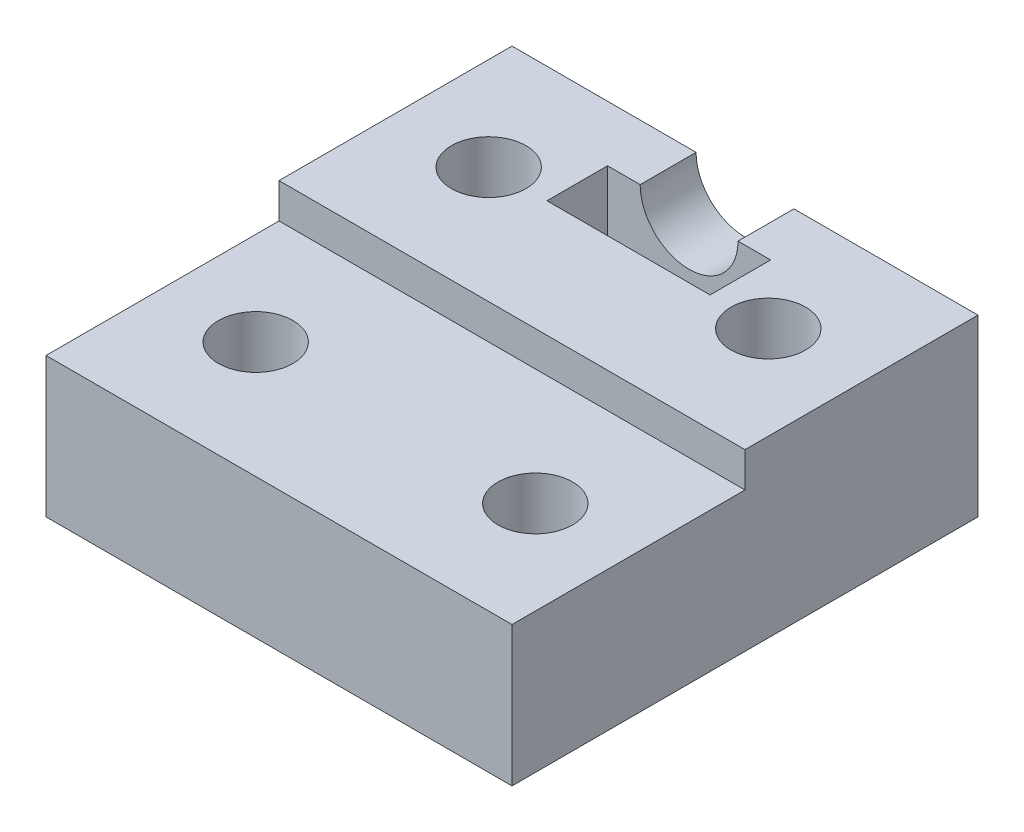
SolidWorks part; units mm, degrees
ref_plane "Front Plane" through (0, 0, 0) normal (0, 0, 1) x (1, 0, 0)
ref_plane "Top Plane" through (0, 0, 0) normal (0, 1, 0) x (1, 0, 0)
ref_plane "Right Plane" through (0, 0, 0) normal (1, 0, 0) x (0, 0, -1)
sketch "Sketch2" plane through (0, 0, 0) normal (0, 1, 0) x (1, 0, 0)
  line L1 (10, 10) -> (-10, 10)
  line L2 (10, 10) -> (10, -10)
  line L3 (10, -10) -> (-10, -10)
  line L4 (-10, 10) -> (-10, -10)
  line L5 (10, 10) -> (-10, -10) construction
  line L6 (10, -10) -> (-10, 10) construction
  point P0 (0, 0)
  dimension "D1" = 20
  dimension "D2" = 20
extrude "Boss-Extrude1" add sketch "Sketch2" against normal blind 7.5
sketch "Sketch3" plane through (0, 0, 10) normal (0, 0, 1) x (1, 0, 0)
  line L1 (10, 1.5) -> (-10, 1.5)
  line L2 (10, 1.5) -> (10, -1.5)
  line L3 (10, -1.5) -> (-10, -1.5)
  line L4 (-10, 1.5) -> (-10, -1.5)
  line L5 (10, 1.5) -> (-10, -1.5) construction
  line L6 (10, -1.5) -> (-10, 1.5) construction
  point P0 (0, 0)
  dimension "D1" = 3
  dimension "D2" = 20
extrude "Cut-Extrude1" cut sketch "Sketch3" against normal blind 10
ref_plane "Plane1" through (0, 0, -5) normal (0, 0, 1) x (1, 0, 0)
sketch "Sketch4" plane through (0, 0, -5) normal (0, 0, 1) x (1, 0, 0)
  line L1 (-3.5, 3.5) -> (3.5, 3.5)
  line L2 (-3.5, 3.5) -> (-3.5, -3.5)
  line L3 (-3.5, -3.5) -> (3.5, -3.5)
  line L4 (3.5, 3.5) -> (3.5, -3.5)
  line L5 (-3.5, 3.5) -> (3.5, -3.5) construction
  line L6 (-3.5, -3.5) -> (3.5, 3.5) construction
  point P0 (0, 0)
  dimension "D1" = 7
  dimension "D2" = 7
extrude "Cut-Extrude2" cut sketch "Sketch4" against normal blind 2.6
sketch "Sketch5" plane through (0, 0, -5) normal (0, 0, 1) x (1, 0, 0)
  circle A0 centre (0, 0) radius 2.1
  dimension "D1" = 4.2
extrude "Cut-Extrude3" cut sketch "Sketch5" against normal through all contours A0
sketch "Sketch6" plane through (0, -1.5, 0) normal (0, 1, 0) x (1, 0, 0)
  line L0 (0, 10) -> (0, -10) construction
  line L1 (2.1, 10) -> (-2.1, 10) construction
  line L2 (-10, -10) -> (10, -10) construction
  line L3 (-10, -5) -> (10, -5) construction
  line L4 (-10, 10) -> (-10, 0) construction
  line L5 (10, 0) -> (10, 10) construction
  point P12 (-6, -5)
  point P13 (6, -5)
  dimension "D1" = 5
  dimension "D2" = 12
hole_wizard "Ø3.1 (3.1) Diameter Hole1" positions "Sketch7" profile "Sketch8" hole size "Ø3.1" standard "ISO" end condition through all
sketch "Sketch7" plane through (0, -1.5, 0) normal (0, 1, 0) x (1, 0, 0)
  point P0 (-6, -5)
  point P3 (6, -5)
sketch "Sketch8" plane through (-6, -1.5, 5) normal (1, 0, 0) x (0, 0, 1)
  line L0 (0, 0) -> (0, 6)
  line L1 (0, 6) -> (1.6, 6)
  line L2 (1.6, 6) -> (1.6, 0)
  line L5 (1.6, 0) -> (0, 0)
  line L11 (0, -6.35) -> (0, 107.95) construction
  dimension "Thru Hole Dia." = 3.2
  dimension "Thru Hole Depth" = 6
sketch "Sketch9" plane through (0, 0, 0) normal (0, 1, 0) x (1, 0, 0)
  line L0 (-10, 5) -> (10, 5) construction
  line L1 (-10, 10) -> (-10, 0) construction
  line L2 (10, 0) -> (10, 10) construction
  line L3 (0, 10) -> (0, -10) construction
  line L4 (2.1, 10) -> (-2.1, 10) construction
  line L5 (-10, -10) -> (10, -10) construction
  line L6 (-2.1, 10) -> (-10, 10) construction
  point P14 (-6, 5)
  point P15 (6, 5)
  dimension "D1" = 5
  dimension "D2" = 12
hole_wizard "Ø3.1 (3.1) Diameter Hole2" positions "Sketch10" profile "Sketch11" hole size "Ø3.1" standard "ISO" end condition through all
sketch "Sketch10" plane through (0, 0, 0) normal (0, 1, 0) x (1, 0, 0)
  point P0 (-6, 5)
  point P3 (6, 5)
sketch "Sketch11" plane through (-6, 0, -5) normal (1, 0, 0) x (0, 0, 1)
  line L0 (0, 0) -> (0, 7.5)
  line L1 (0, 7.5) -> (1.6, 7.5)
  line L2 (1.6, 7.5) -> (1.6, 0)
  line L5 (1.6, 0) -> (0, 0)
  line L11 (0, -6.35) -> (0, 107.95) construction
  dimension "Thru Hole Dia." = 3.2
  dimension "Thru Hole Depth" = 7.5
